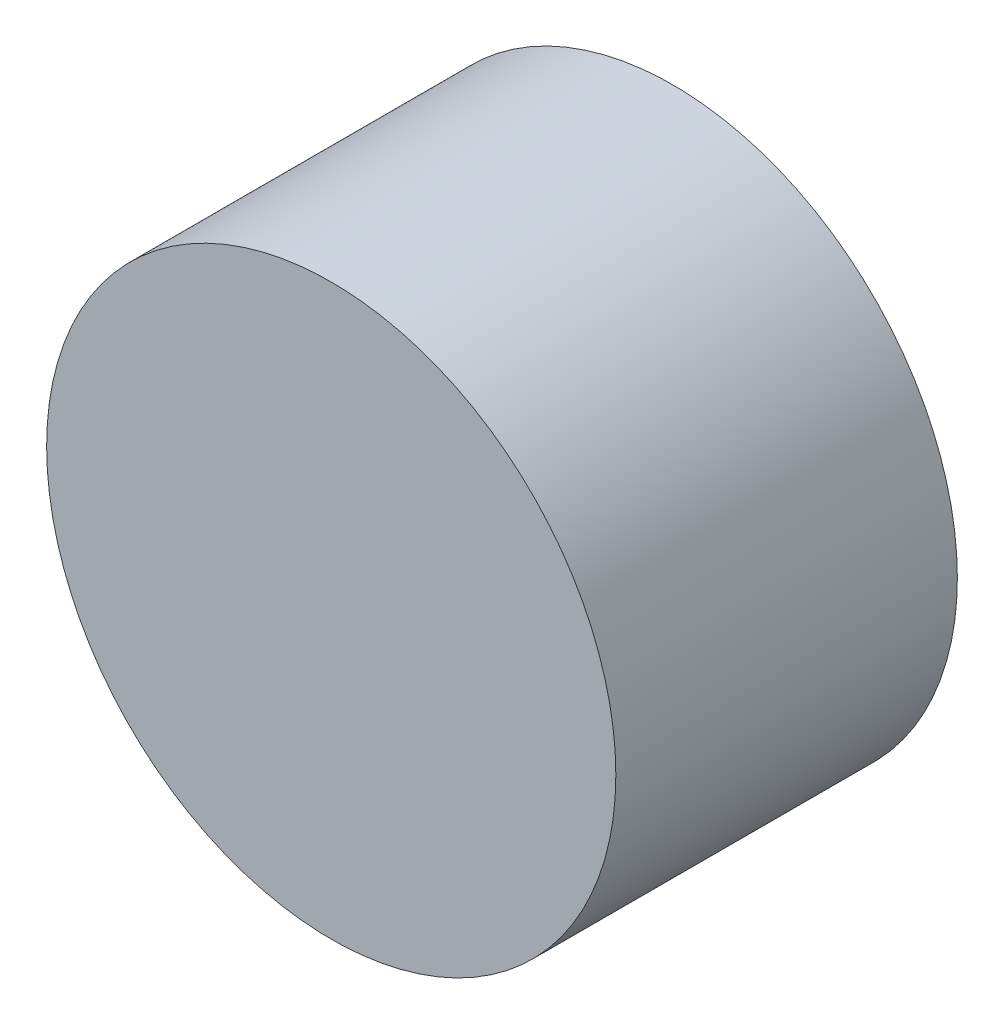
SolidWorks part; units mm, degrees
ref_plane "Front Plane" through (0, 0, 0) normal (0, 0, 1) x (1, 0, 0)
ref_plane "Top Plane" through (0, 0, 0) normal (0, 1, 0) x (1, 0, 0)
ref_plane "Right Plane" through (0, 0, 0) normal (1, 0, 0) x (0, 0, -1)
sketch "Sketch1" plane through (0, 0, 0) normal (0, 0, 1) x (1, 0, 0)
  circle A0 centre (-24.6, 10.8442) radius 2.55 construction
  circle A1 centre (-24.6, 10.8442) radius 2.55 construction
  circle A2 centre (-24.6, 10.8442) radius 2.5
  dimension "D1" = 5
extrude "Boss-Extrude1" add sketch "Sketch1" against normal blind 3
